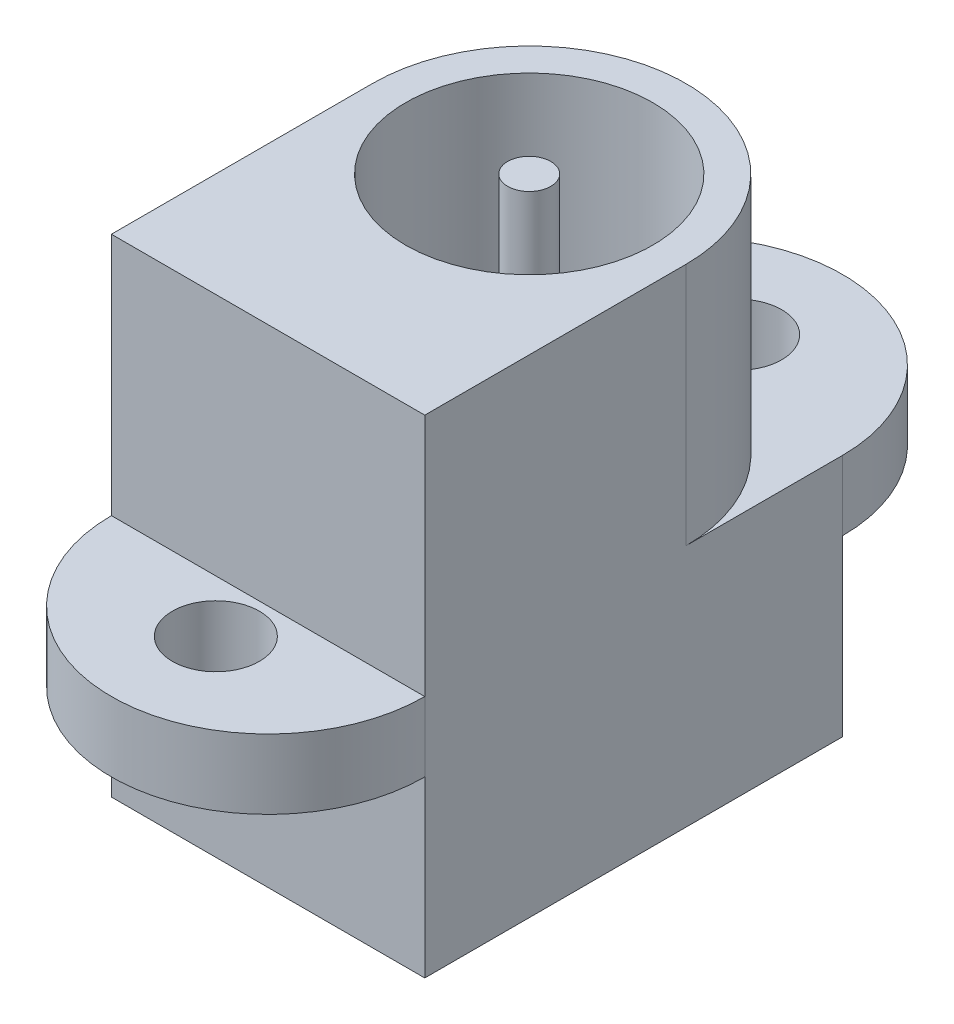
SolidWorks part; units mm, degrees
material "ABS"
ref_plane "Plan de face" through (0, 0, 0) normal (0, 0, 1) x (1, 0, 0)
ref_plane "Plan de dessus" through (0, 0, 0) normal (0, 1, 0) x (1, 0, 0)
ref_plane "Plan de droite" through (0, 0, 0) normal (1, 0, 0) x (0, 0, -1)
sketch "Esquisse1" plane through (0, 0, 0) normal (0, 1, 0) x (1, 0, 0)
  line L0 (-4.5, 6) -> (-4.5, -6)
  line L1 (4.5, -6) -> (4.5, 6)
  line L2 (-4.5, 0) -> (4.5, 0) construction
  arc A0 (-4.5, -6) -> (4.5, -6) centre (0, -6) ccw
  arc A1 (4.5, 6) -> (-4.5, 6) centre (0, 6) ccw
  circle A2 centre (0, 7.5) radius 1.25
  circle A3 centre (0, -7.5) radius 1.25
  dimension "D2" = 12
  dimension "D3" = 2.5
  dimension "D1" = 9
  dimension "D4" = 15
extrude "Extrusion1" add sketch "Esquisse1" against normal blind 2
sketch "Esquisse2" plane through (0, 0, 0) normal (0, 1, 0) x (-1, 0, 0)
  line L0 (4.5, 6) -> (-4.5, 6)
  line L1 (-4.5, 6) -> (-4.5, -1.5)
  line L2 (-4.5, 6) -> (-4.5, -6) construction
  line L3 (4.5, -6) -> (4.5, 6) construction
  line L4 (4.5, -1.5) -> (4.5, 6)
  arc A0 (-4.5, -1.5) -> (4.5, -1.5) centre (0, -1.5) ccw
  circle A1 centre (0, -1.5) radius 3.5489
  circle A2 centre (0, -1.5) radius 0.6192
  line M8 (4.5, -6) -> (4.5, 6)
  line M10 (-4.5, 6) -> (-4.5, -6)
  dimension "D1" = 12
extrude "Extrusion2" add sketch "Esquisse2" along normal blind 7 contours A0 L0 A1 M10 M8 | A2
sketch "Esquisse3" plane through (0, -2, 0) normal (0, -1, 0) x (1, 0, 0)
  line L1 (4.5, 6) -> (-4.5, 6)
  line L2 (4.5, 6) -> (4.5, -6)
  line L3 (4.5, -6) -> (-4.5, -6)
  line L4 (-4.5, 6) -> (-4.5, -6)
extrude "Extrusion3" add sketch "Esquisse3" along normal blind 5
